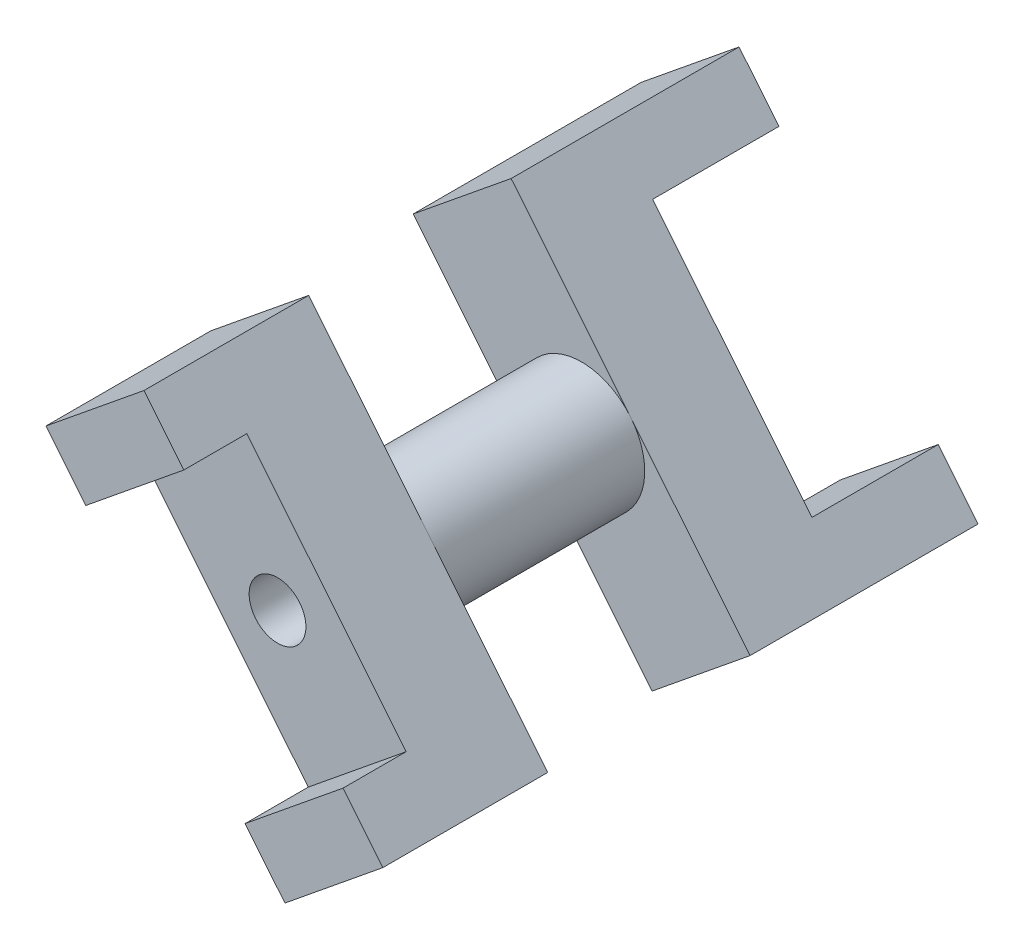
SolidWorks part; units mm, degrees
ref_plane "Front Plane" through (0, 0, 0) normal (0, 0, 1) x (1, 0, 0)
ref_plane "Top Plane" through (0, 0, 0) normal (0, 1, 0) x (1, 0, 0)
ref_plane "Right Plane" through (0, 0, 0) normal (1, 0, 0) x (0, 0, -1)
sketch "Sketch1" plane through (0, 0, 0) normal (0, 0, 1) x (1, 0, 0)
  circle A0 centre (0, 0) radius 3
  circle A1 centre (0, 0) radius 1.35
  dimension "D1" = 6
  dimension "D2" = 2.7
extrude "Boss-Extrude1" add sketch "Sketch1" along normal up to surface (19.2934 mm away)
ref_plane "Plane1" through (-2.3273, -1.8931, 0) normal (-0.7758, -0.631, 0) x (0, 0, 1)
sketch "Sketch2" plane through (-2.3273, -1.8931, 0) normal (-0.7758, -0.631, 0) x (0, 0, 1)
  line L5 (19.2934, 3) -> (0, 3) construction
  line L6 (14.4573, 3) -> (14.4573, -3)
  line L7 (14.4573, 0) -> (19.2934, 0) construction
  line L8 (19.2934, -3) -> (19.2934, 3) construction
  line L9 (19.2934, -3) -> (19.2934, 3)
  line L16 (19.2934, 9) -> (22.2934, 9)
  line L17 (22.2934, 9) -> (22.2934, 6)
  line L18 (22.2934, 6) -> (19.2934, 6)
  line L19 (19.2934, 6) -> (19.2934, 3)
  line L20 (19.2934, 9) -> (14.4573, 9)
  line L21 (14.4573, 9) -> (14.4573, 3)
  line L22 (9.6467, 3) -> (9.6467, -6.9086) construction
  line L23 (14.4573, -9) -> (14.4573, -3)
  line L24 (19.2934, -9) -> (14.4573, -9)
  line L25 (19.2934, -6) -> (19.2934, -3)
  line L26 (22.2934, -6) -> (19.2934, -6)
  line L27 (22.2934, -9) -> (22.2934, -6)
  line L28 (19.2934, -9) -> (22.2934, -9)
  line L29 (4.8361, 0) -> (0, 0) construction
  line L30 (0, -9) -> (-3, -9)
  line L32 (-3, -6) -> (0, -6)
  line L33 (0, -6) -> (0, -3)
  line L34 (0, -9) -> (4.8361, -9)
  line L35 (4.8361, -9) -> (4.8361, -3)
  line L36 (4.8361, 9) -> (4.8361, 3)
  line L37 (0, 9) -> (4.8361, 9)
  line L38 (0, 6) -> (0, 3)
  line L39 (-3, 6) -> (0, 6)
  line L41 (0, 9) -> (-3, 9)
  line L42 (0, -3) -> (0, 3)
  line L43 (4.8361, 3) -> (4.8361, -3)
  line L44 (-3, 9) -> (-6, 9) construction
  line L45 (-6, 9) -> (-6, 6)
  line L46 (-6, 6) -> (-3, 6)
  line L47 (-3, 9) -> (-6, 9)
  line L48 (-3, -6) -> (-6, -6)
  line L49 (-6, -6) -> (-6, -9)
  line L50 (-6, -9) -> (-3, -9)
extrude "Boss-Extrude2" add sketch "Sketch2" against normal up to surface (6 mm away)
sketch "Sketch3" plane through (0, 0, 19.2934) normal (0, 0, 1) x (1, 0, 0)
  circle A0 centre (0, 0) radius 1.35
extrude "Cut-Extrude1" cut sketch "Sketch3" against normal blind 4
sketch "Sketch4" plane through (0, 0, 0) normal (0, 0, -1) x (-1, 0, 0)
  circle A0 centre (0, 0) radius 1.35
extrude "Cut-Extrude2" cut sketch "Sketch4" against normal blind 4
